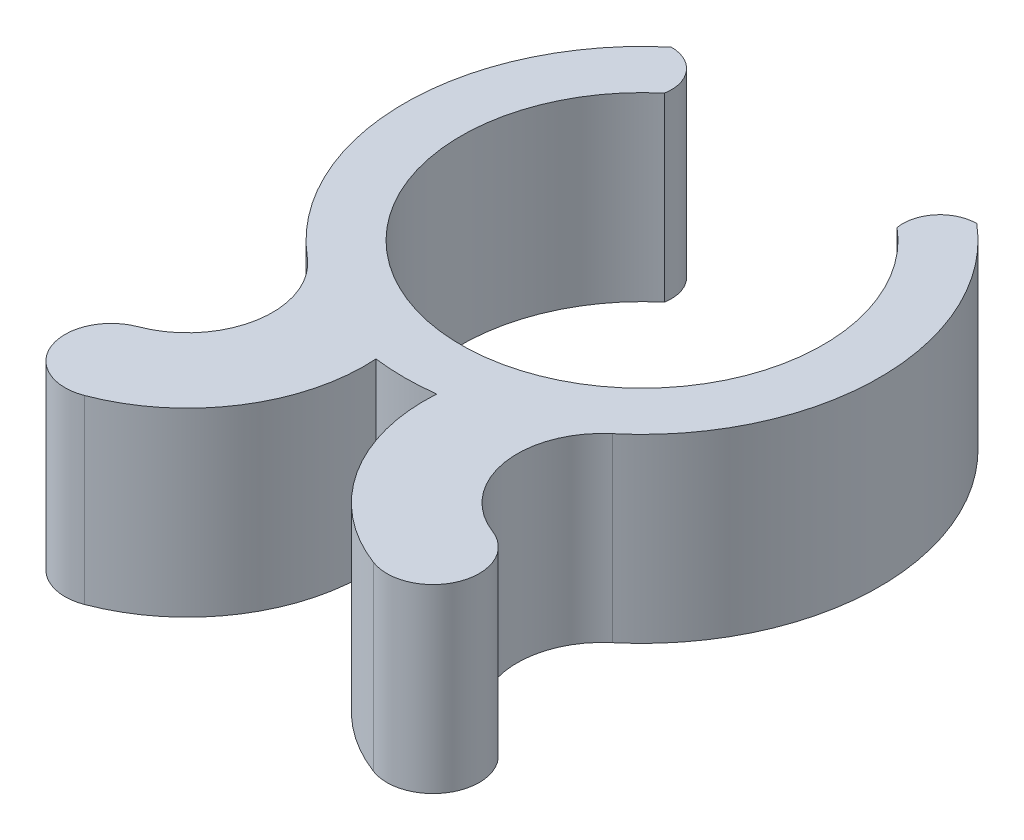
SolidWorks part; units mm, degrees
ref_plane "Front Plane" through (0, 0, 0) normal (0, 0, 1) x (1, 0, 0)
ref_plane "Top Plane" through (0, 0, 0) normal (0, 1, 0) x (1, 0, 0)
ref_plane "Right Plane" through (0, 0, 0) normal (1, 0, 0) x (0, 0, -1)
sketch "Esquisse4" plane through (0, 0, 0) normal (0, 1, 0) x (1, 0, 0)
  line L0 (-5.1423, 6.1284) -> (5.1423, 6.1284) construction
  line L1 (-6.7493, 8.0435) -> (6.7493, 8.0435) construction
  line L2 (-6.7493, 8.0435) -> (-5.1423, 6.1284) construction
  line L3 (-5.1423, 6.1284) -> (0, 0) construction
  line L4 (0, 0) -> (6.7493, 8.0435) construction
  line L5 (0, 0) -> (-6.7493, -8.0435) construction
  line L6 (0, 0) -> (75.2143, -89.6369) construction
  line L7 (-6.7493, -8.0435) -> (-9.1655, -10.923) construction
  arc A0 (5.1423, 6.1284) -> (-5.1423, 6.1284) centre (0, 0) cw
  arc A1 (6.7493, 8.0435) -> (-6.7493, 8.0435) centre (0, 0) cw
  arc A2 (-6.7493, 8.0435) -> (-5.1423, 6.1284) centre (-6.7493, 6.4117) cw
  arc A3 (6.7493, 8.0435) -> (5.1423, 6.1284) centre (6.7493, 6.4117) ccw
  arc A4 (-6.7493, -8.0435) -> (-7.8346, -14.4386) centre (-9.1655, -10.923) cw
  arc A5 (-1.9977, -7.7466) -> (-6.3896, -18.2553) centre (-9.1655, -10.923) cw
  arc A6 (-6.3896, -18.2553) -> (-7.8346, -14.4386) centre (-7.1121, -16.3469) cw
  point P8 (-131.7715, -157.0391)
  point P13 (-110.0264, -142.4577)
  point P14 (-6.2703, -16.8726)
  point P15 (0, 0)
  point P19 (-16.8594, -37.0136)
  point P20 (-7.6201, -16.7132)
  point P21 (-7.8346, -14.4386)
  dimension "D3" = 8
  dimension "D1" = 2.5
  dimension "D2" = 80
ref_plane "Plan1" through (0, 0, 0) normal (1, 0, 0) x (0, 0, -1)
extrude "Boss.-Extru.1" add sketch "Esquisse4" along normal blind 8 contours A5 A0 A2 A1 | A0 A5 A1 A3 | A6 A5 A1 A4
mirror "Symétrie1" about plane through (0, 0, 0) normal (1, 0, 0) of "Boss.-Extru.1"
